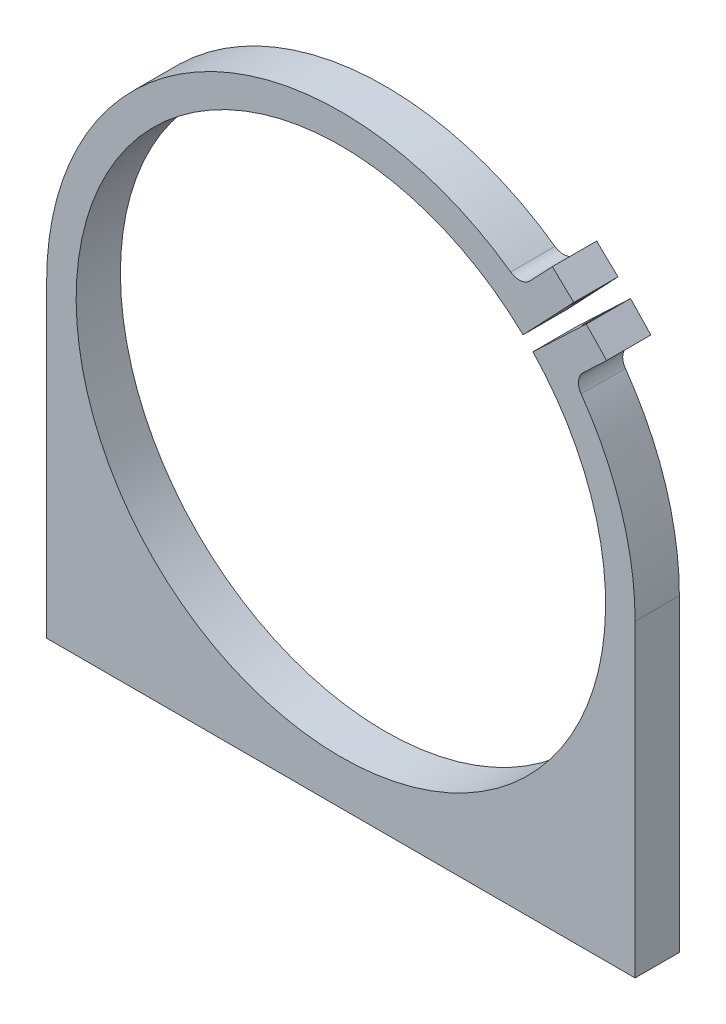
SolidWorks part; units mm, degrees
ref_plane "Front Plane" through (0, 0, 0) normal (0, 0, 1) x (1, 0, 0)
ref_plane "Top Plane" through (0, 0, 0) normal (0, 1, 0) x (1, 0, 0)
ref_plane "Right Plane" through (0, 0, 0) normal (1, 0, 0) x (0, 0, -1)
sketch "Sketch1" plane through (0, 0, 0) normal (0, 0, 1) x (1, 0, 0)
  line L0 (-63.3222, 0) -> (-63.3222, -66.4972)
  line L1 (-63.3222, -66.4972) -> (63.3222, -66.4972)
  line L2 (63.3222, -66.4972) -> (63.3222, 0)
  line L4 (0, 0) -> (44.7756, 44.7756) construction
  line L5 (-1.4665, 1.4665) -> (43.3091, 46.242) construction
  line L8 (0, 2.9329) -> (0, 0) construction
  line L14 (-1.4665, 1.4665) -> (0, 2.9329)
  line L15 (41.3262, 39.2171) -> (52.8207, 50.1249)
  line L16 (52.8207, 50.1249) -> (57.1917, 45.5188)
  line L17 (57.1917, 45.5188) -> (52.125, 40.7106)
  line L18 (45.5188, 57.1917) -> (40.7106, 52.125)
  line L19 (50.1249, 52.8207) -> (45.5188, 57.1917)
  line L20 (39.2171, 41.3262) -> (50.1249, 52.8207)
  arc A0 (39.2171, 41.3262) -> (41.3262, 39.2171) centre (0, 0) ccw
  arc A1 (63.3222, 0) -> (51.7143, 36.5423) centre (0, 0) ccw
  arc A2 (36.5423, 51.7143) -> (-63.3222, 0) centre (0, 0) ccw
  arc A5 (52.125, 40.7106) -> (51.7143, 36.5423) centre (54.328, 38.3892) ccw
  arc A6 (40.7106, 52.125) -> (36.5423, 51.7143) centre (38.3892, 54.328) cw
  point P19 (-10.0997, 62.5116)
  point P25 (51.07, 25.2525)
  point P35 (0, 0)
  point P36 (50.1591, 27.0167)
  point P37 (51.6899, 23.9581)
  point P38 (50.154, 27.026)
  dimension "D1" = 113.9444
  dimension "D12" = 3.2004
  dimension "D2" = 6.35
  dimension "D3" = 3.175
  dimension "D8" = 45
  dimension "D11" = 6.35
  dimension "D13" = 6.985
  dimension "D9" = 1.5
extrude "Boss-Extrude1" add sketch "Sketch1" along normal blind 9.525 contours L0 L1 L2 A1 A5 L17 L16 L15 A0 L20 L19 L18 A6 A2
hole_wizard "#10-32 Tapped Hole2" positions "Sketch7" profile "Sketch8" tap size "#10-32" standard "ANSI Inch"
sketch "Sketch7" plane through (0, -66.4972, 0) normal (0, -1, 0) x (-1, 0, 0)
  line L0 (-41.275, -4.7625) -> (41.275, -4.7625) construction
  line L2 (0, 0) -> (0, -4.7625) construction
  line L3 (63.3222, 0) -> (-63.3222, 0) construction
  line L5 (63.3222, -9.525) -> (-63.3222, -9.525) construction
  point P0 (-41.275, -4.7625)
  point P2 (41.275, -4.7625)
  dimension "D1" = 82.55
sketch "Sketch8" plane through (41.275, -66.4972, 4.7625) normal (1, 0, 0) x (0, 0, -1)
  line L0 (0, 0) -> (0, 14.5796)
  line L1 (0, 14.5796) -> (2.0193, 14.5796)
  line L2 (2.0193, 14.5796) -> (2.0193, 0)
  line L5 (2.0193, 0) -> (0, 0)
  line L10 (0, 14.5796) -> (-2.0193, 14.5796) construction
  line L11 (0, -6.35) -> (0, 107.95) construction
  dimension "Tap Drill Dia." = 4.0386
  dimension "Tap Drill Depth" = 14.5796
  dimension "Drill Angle" = 180
cosmetic thread "Hole Thread2" parameters "D1"=12.192, "D2"=4.826
cosmetic thread "Hole Thread3" parameters "D1"=12.192, "D2"=4.826
sketch "Sketch9" plane through (4.3711, -4.6061, 0) normal (0.6884, -0.7254, 0) x (0.7254, 0.6884, 0)
  line L0 (72.8185, 9.525) -> (72.8185, 0) construction
  line L1 (72.8185, 4.7625) -> (65.8335, 4.7625) construction
  line L2 (65.8335, 9.525) -> (65.8335, 0) construction
  line L3 (69.326, 9.525) -> (69.326, 0) construction
  line L4 (72.8185, 9.525) -> (65.8335, 9.525) construction
  line L5 (72.8185, 0) -> (65.8335, 0) construction
  point P0 (69.326, 4.7625)
  point P13 (70.931, 1.9515)
  point P14 (0, 0)
  point P15 (69.326, 4.7625)
hole_wizard "#6 (0.204) Diameter Hole1" positions "3DSketch1" profile "Sketch11" hole size "#6" standard "ANSI Inch" end condition through all
sketch3d "3DSketch1"
  point P0 (54.6583, 43.1147, 4.7625)
sketch "Sketch11" plane through (54.6583, 43.1147, 4.7625) normal (0, 0, 1) x (0.7254, 0.6884, 0)
  line L0 (0, 0) -> (0, 95.8704)
  line L1 (0, 95.8704) -> (2.5908, 95.8704)
  line L2 (2.5908, 95.8704) -> (2.5908, 0)
  line L5 (2.5908, 0) -> (0, 0)
  line L11 (0, -6.35) -> (0, 107.95) construction
  dimension "Thru Hole Dia." = 5.1816
  dimension "Thru Hole Depth" = 95.8704
equation "\"outer tube diameter\"= 4.486"
equation "\"D1@Sketch1\"=\"outer tube diameter\""
